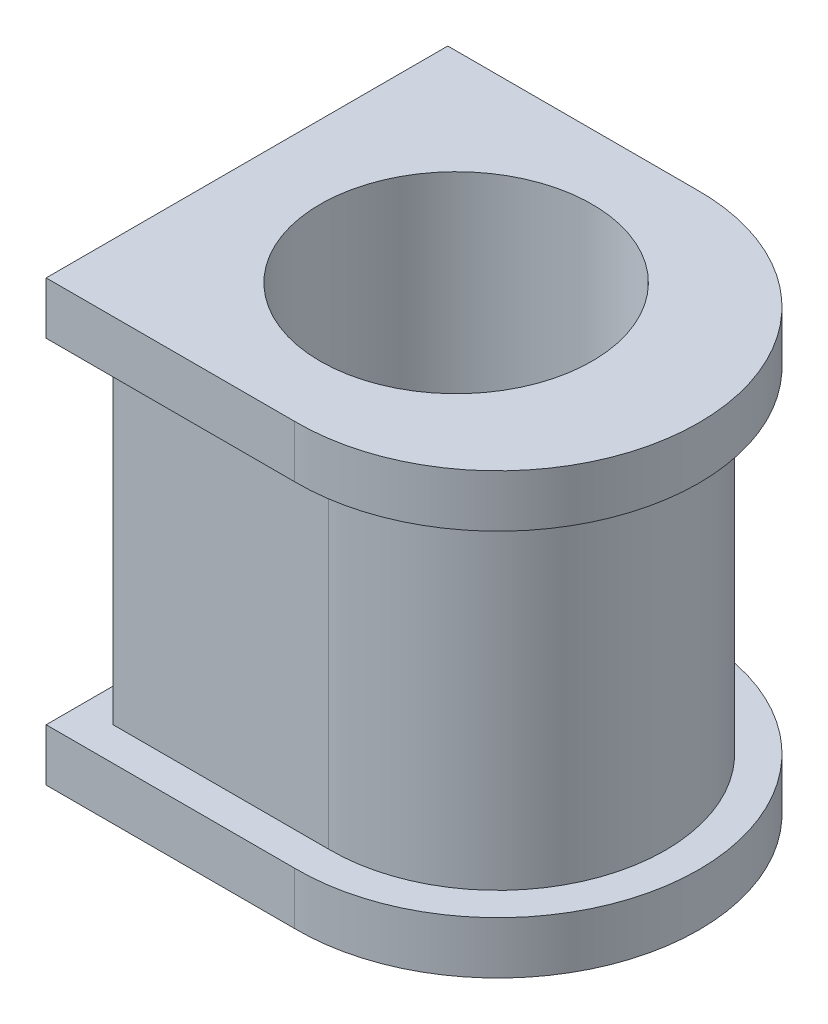
SolidWorks part; units mm, degrees
ref_plane "Front Plane" through (0, 0, 0) normal (0, 0, 1) x (1, 0, 0)
ref_plane "Top Plane" through (0, 0, 0) normal (0, 1, 0) x (1, 0, 0)
ref_plane "Right Plane" through (0, 0, 0) normal (1, 0, 0) x (0, 0, -1)
sketch "Sketch1" plane through (0, 0, 0) normal (0, 1, 0) x (1, 0, 0)
  line L1 (-26, 40) -> (25.4505, 40)
  line L2 (-26, 40) -> (-26, -40)
  line L3 (-26, -40) -> (25.4505, -40)
  arc A0 (25.4505, -40) -> (25.4505, 40) centre (26, 0) ccw
  circle A1 centre (16, 0) radius 32.5
  point P0 (0, 0)
  dimension "D3" = 65
  dimension "D1" = 10
  dimension "D2" = 80
extrude "Boss-Extrude1" add sketch "Sketch1" along normal blind 80
sketch "Sketch2" plane through (0, 80, 0) normal (0, 1, 0) x (1, 0, 0)
  line L6 (-34, 48) -> (-34, -48)
  line L7 (-34, -48) -> (25.398, -48)
  line L8 (25.398, 48) -> (-34, 48)
  line L9 (-34, 48) -> (-34, -48)
  line L10 (-34, -48) -> (25.398, -48)
  line L11 (25.398, 48) -> (-34, 48)
  circle A1 centre (16, 0) radius 32.5 construction
  arc A2 (25.398, -48) -> (25.398, 48) centre (26, 0) ccw
  arc A3 (25.398, -48) -> (25.398, 48) centre (26, 0) ccw
  circle A4 centre (16, 0) radius 32.5
  dimension "D1" = 8
extrude "Boss-Extrude2" add sketch "Sketch2" along normal blind 12.5
ref_plane "Plane1" through (0, 40, 0) normal (0, 1, 0) x (1, 0, 0)
mirror "Mirror1" about plane through (0, 40, 0) normal (0, 1, 0) of "Boss-Extrude2"
